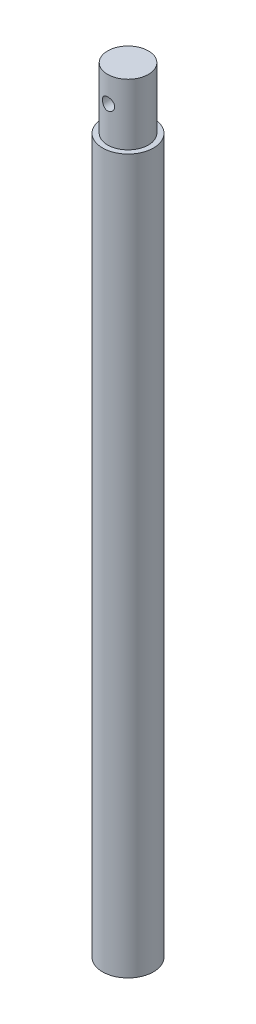
SolidWorks part; units mm, degrees
ref_plane "Front Plane" through (0, 0, 0) normal (0, 0, 1) x (1, 0, 0)
ref_plane "Top Plane" through (0, 0, 0) normal (0, 1, 0) x (1, 0, 0)
ref_plane "Right Plane" through (0, 0, 0) normal (1, 0, 0) x (0, 0, -1)
sketch "Sketch2" plane through (0, 0, 0) normal (0, 0, 1) x (1, 0, 0)
  line L0 (0, 0) -> (0, 57.2523) construction
  line L1 (0, 0) -> (12.5, 0)
  line L2 (12.5, 0) -> (12.5, 350)
  line L3 (12.5, 350) -> (10, 350)
  line L4 (10, 350) -> (10, 380)
  line L5 (10, 380) -> (0, 380)
  line L6 (0, 0) -> (0, 380)
  dimension "D1" = 25
  dimension "D2" = 350
  dimension "D3" = 30
  dimension "D4" = 20
  dimension "D5" = 380
revolve "Revolve1" add sketch "Sketch2" angle 360 about L0
sketch "Sketch3" plane through (0, 0, 0) normal (0, 0, 1) x (1, 0, 0)
  line L1 (0, -55) -> (0, 55) construction
  line L2 (10, 380) -> (-10, 380) construction
  circle A0 centre (0, 367.5) radius 3
  dimension "D2" = 6
  dimension "D1" = 12.5
extrude "Cut-Extrude1" cut sketch "Sketch3" against normal mid plane 50
